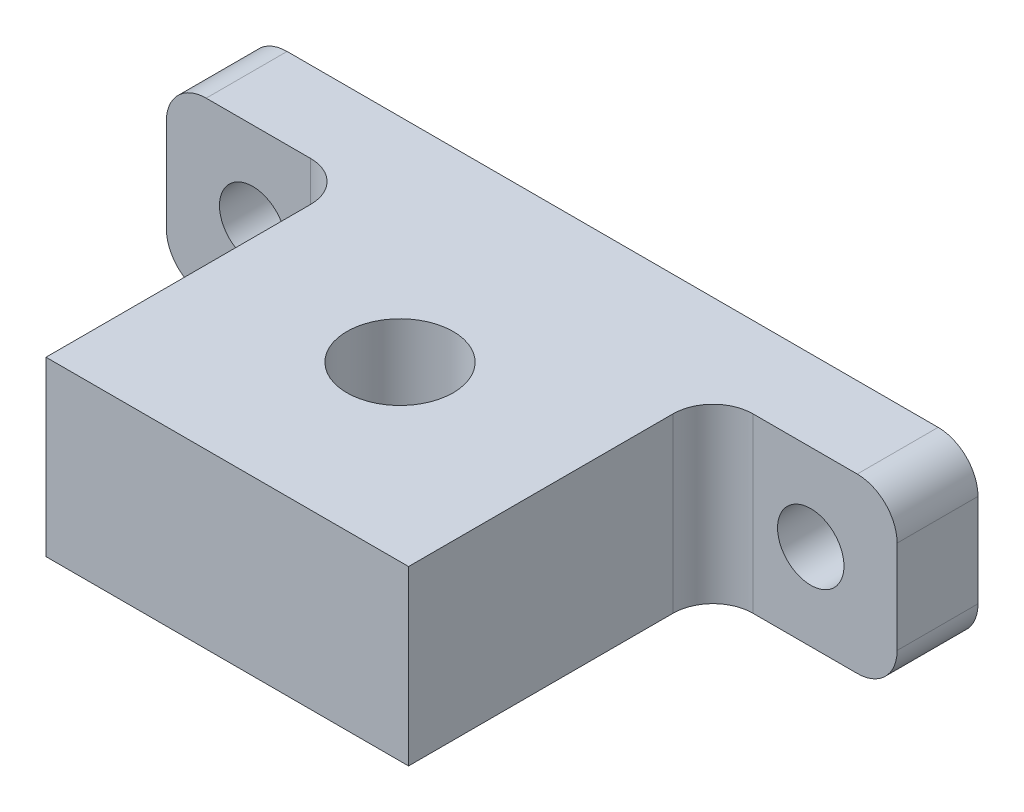
SolidWorks part; units mm, degrees
material "AISI 1020"
ref_plane "Plano frontal" through (0, 0, 0) normal (0, 0, 1) x (1, 0, 0)
ref_plane "Plano superior" through (0, 0, 0) normal (0, 1, 0) x (1, 0, 0)
ref_plane "Plano direito" through (0, 0, 0) normal (1, 0, 0) x (0, 0, -1)
sketch "Esboço2" plane through (0, 0, 0) normal (0, 0, 1) x (1, 0, 0)
  line L0 (-27.5, -3.5) -> (-27.5, 3.5)
  line L1 (-24.5, -6.5) -> (24.5, -6.5)
  line L2 (-24.5, 6.5) -> (24.5, 6.5)
  line L3 (27.5, -3.5) -> (27.5, 3.5)
  line L4 (-27.5, -6.5) -> (27.5, 6.5) construction
  line L5 (-27.5, 6.5) -> (27.5, -6.5) construction
  line L6 (0, 0) -> (0, 6.5) construction
  circle A0 centre (-21, 0) radius 2.5
  circle A1 centre (21, 0) radius 2.5
  arc A2 (24.5, 6.5) -> (27.5, 3.5) centre (24.5, 3.5) cw
  arc A3 (24.5, -6.5) -> (27.5, -3.5) centre (24.5, -3.5) ccw
  arc A4 (-24.5, -6.5) -> (-27.5, -3.5) centre (-24.5, -3.5) cw
  arc A5 (-27.5, 3.5) -> (-24.5, 6.5) centre (-24.5, 3.5) cw
  point P1 (0, 0)
  dimension "D3" = 6.5
  dimension "D5" = 5
  dimension "D6" = 3
  dimension "D7" = 3
  dimension "D1" = 13
  dimension "D2" = 55
  dimension "D4" = 42
extrude "Ressalto-extrusão1" add sketch "Esboço2" along normal blind 29
sketch "Esboço3" plane through (0, -6.5, 0) normal (0, -1, 0) x (1, 0, 0)
  line L0 (0, 0) -> (0, 29) construction
  line L1 (-27.5, 29) -> (-13.6432, 29)
  line L2 (-27.5, 29) -> (-27.5, 6.0871)
  line L3 (-27.5, 6.0871) -> (-16.6432, 6.0871)
  line L4 (-13.6432, 29) -> (-13.6432, 9.0871)
  line L5 (-24.5, 0) -> (24.5, 0) construction
  line L6 (-24.5, 29) -> (24.5, 29) construction
  line L7 (27.5, 6.0871) -> (16.6432, 6.0871)
  line L8 (13.6432, 29) -> (13.6432, 9.0871)
  line L9 (27.5, 29) -> (13.6432, 29)
  line L10 (27.5, 29) -> (27.5, 6.0871)
  circle A1 centre (0, 16) radius 4
  arc A2 (-16.6432, 6.0871) -> (-13.6432, 9.0871) centre (-16.6432, 9.0871) ccw
  arc A3 (16.6432, 6.0871) -> (13.6432, 9.0871) centre (16.6432, 9.0871) cw
  point P19 (-13.6432, 6.0871)
  point P22 (13.6432, 6.0871)
  dimension "D1" = 16
  dimension "D4" = 8
  dimension "D5" = 3
  dimension "D2" = 22.9129
  dimension "D3" = 13.8568
extrude "Corte-extrusão1" cut sketch "Esboço3" against normal through all
